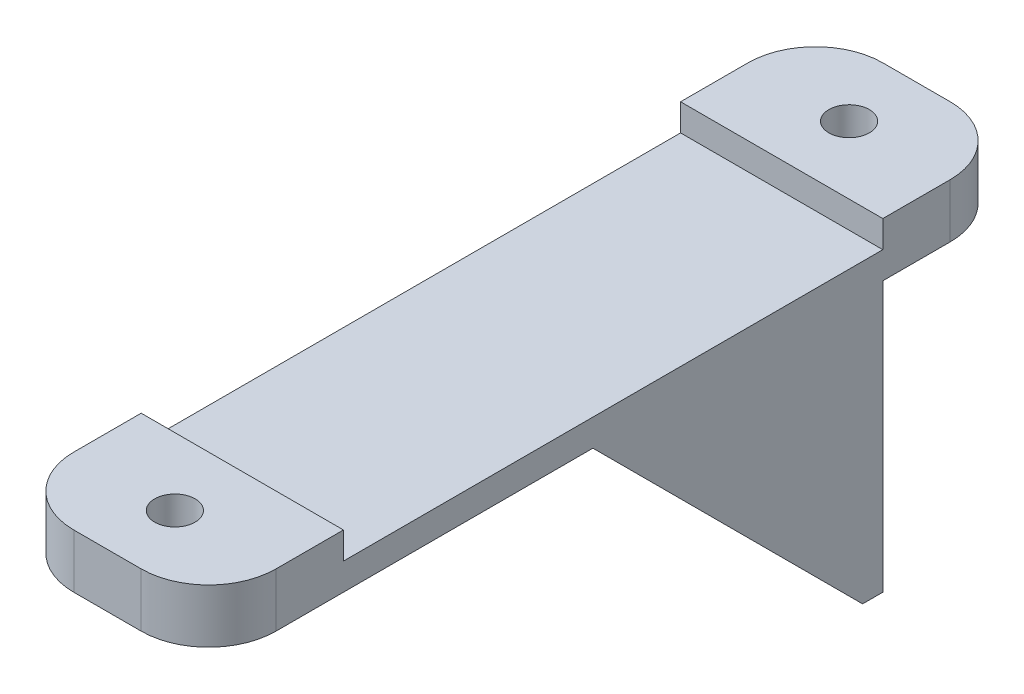
SolidWorks part; units mm, degrees
ref_plane "Front Plane" through (0, 0, 0) normal (0, 0, 1) x (1, 0, 0)
ref_plane "Top Plane" through (0, 0, 0) normal (0, 1, 0) x (1, 0, 0)
ref_plane "Right Plane" through (0, 0, 0) normal (1, 0, 0) x (0, 0, -1)
sketch "Sketch1" plane through (0, 0, 0) normal (0, 1, 0) x (1, 0, 0)
  line L1 (0, 0) -> (30, 0)
  line L2 (0, 0) -> (0, 120)
  line L3 (0, 120) -> (30, 120)
  line L4 (30, 0) -> (30, 120)
  dimension "D1" = 120
  dimension "D2" = 30
extrude "Boss-Extrude1" add sketch "Sketch1" along normal blind 8
sketch "Sketch2" plane through (0, 8, 0) normal (0, 1, 0) x (1, 0, 0)
  line L0 (0, 120) -> (0, 0) construction
  line L1 (30, 100) -> (0, 100)
  line L2 (30, 100) -> (30, 20)
  line L3 (30, 20) -> (0, 20)
  line L4 (0, 100) -> (0, 20)
  line L5 (30, 100) -> (0, 20) construction
  line L6 (30, 20) -> (0, 100) construction
  line L7 (30, 120) -> (0, 120) construction
  point P0 (15, 60)
  dimension "D1" = 80
  dimension "D2" = 30
  dimension "D3" = 20
extrude "Cut-Extrude1" cut sketch "Sketch2" against normal blind 4
sketch "Sketch3" plane through (0, 0, 0) normal (0, -1, 0) x (1, 0, 0)
  line L0 (0, -120) -> (0, 0) construction
  line L1 (0, -97) -> (30, -97)
  line L2 (0, -97) -> (0, -100)
  line L3 (0, -100) -> (30, -100)
  line L4 (30, -97) -> (30, -100)
  line L5 (30, 0) -> (30, -120) construction
  line L7 (30, -120) -> (0, -120) construction
  dimension "D1" = 20
  dimension "D2" = 3
extrude "Boss-Extrude2" add sketch "Sketch3" along normal blind 40
sketch "Sketch4" plane through (0, 0, -97) normal (0, 0, 1) x (1, 0, 0)
  line L0 (30, -40) -> (0, -40) construction
  line L1 (0, -40) -> (0, 0) construction
  circle A0 centre (15, -20) radius 8.6
  dimension "D2" = 17.2
  dimension "D3" = 15
  dimension "D1" = 20
extrude "Cut-Extrude2" cut sketch "Sketch4" against normal blind 40
sketch "Sketch5" plane through (30, 0, 0) normal (1, 0, 0) x (0, 0, -1)
  line L0 (97, -40) -> (57, 0)
  line L1 (0, 0) -> (97, 0) construction
  line L3 (97, 0) -> (97, -40)
  line L4 (57, 0) -> (97, 0)
  dimension "D1" = 45
extrude "Boss-Extrude3" add sketch "Sketch5" against normal blind 2.5
sketch "Sketch6" plane through (0, 0, 0) normal (-1, 0, 0) x (0, 0, 1)
  line L0 (-57, 0) -> (-97, -40) construction
  line L1 (-97, 0) -> (0, 0) construction
  line L2 (-97, -40) -> (-97, 0) construction
  line L3 (-57, 0) -> (-97, -40)
  line L4 (-97, 0) -> (-57, 0)
  line L5 (-97, -40) -> (-97, 0)
extrude "Boss-Extrude4" add sketch "Sketch6" against normal blind 2.5
sketch "Sketch7" plane through (0, 0, 0) normal (0, -1, 0) x (-1, 0, 0)
  line L0 (-30, 0) -> (-30, 57) construction
  line L1 (0, 0) -> (-30, 0) construction
  line L2 (-30, 120) -> (0, 120) construction
  line L3 (0, 120) -> (0, 100) construction
  circle A0 centre (-15, 10) radius 3
  circle A1 centre (-15, 110) radius 3
  dimension "D3" = 6
  dimension "D4" = 6
  dimension "D5" = 10
  dimension "D6" = 15
  dimension "D1" = 15
  dimension "D2" = 10
extrude "Cut-Extrude3" cut sketch "Sketch7" against normal through all
fillet "Fillet1" radius 10 4 edges at (30, 4, -120) (0, 4, -120) (30, 4, 0) (0, 4, 0)
